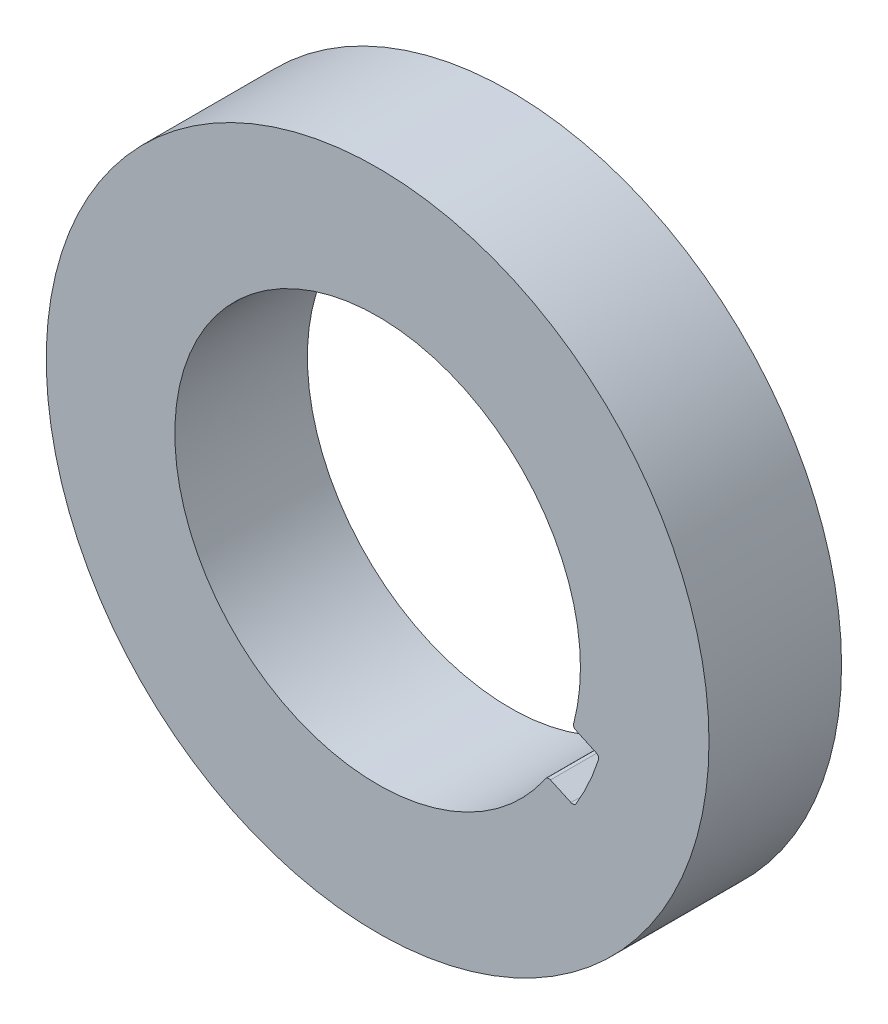
SolidWorks part; units mm, degrees
material "Chêne"
ref_plane "Plan de face" through (0, 0, 0) normal (0, 0, 1) x (1, 0, 0)
ref_plane "Plan de dessus" through (0, 0, 0) normal (0, 1, 0) x (1, 0, 0)
ref_plane "Plan de droite" through (0, 0, 0) normal (1, 0, 0) x (0, 0, -1)
sketch "Esquisse1" plane through (0, 0, 0) normal (0, 0, 1) x (1, 0, 0)
  line L0 (14.953, -4.2772) -> (16.5018, -4.9824)
  line L1 (13.0383, -8.4787) -> (14.587, -9.1845)
  arc A0 (12.6655, -8.5834) -> (14.7874, -3.9272) centre (0, 0) cw
  arc A1 (16.6631, -5.3471) -> (14.968, -9.0669) centre (0, 0) cw
  arc A2 (14.953, -4.2772) -> (14.7874, -3.9272) centre (15.0774, -4.0042) cw
  arc A3 (16.6631, -5.3471) -> (16.5018, -4.9824) centre (16.3774, -5.2555) ccw
  arc A4 (14.587, -9.1845) -> (14.968, -9.0669) centre (14.7114, -8.9115) ccw
  circle A5 centre (0, 0) radius 25
  arc A83 (13.0383, -8.4787) -> (12.6655, -8.5834) centre (12.9139, -8.7517) ccw
  point P116 (0, 0)
  point P374 (0, 0)
extrude "Boss.-Extru.1" add sketch "Esquisse1" along normal blind 10
